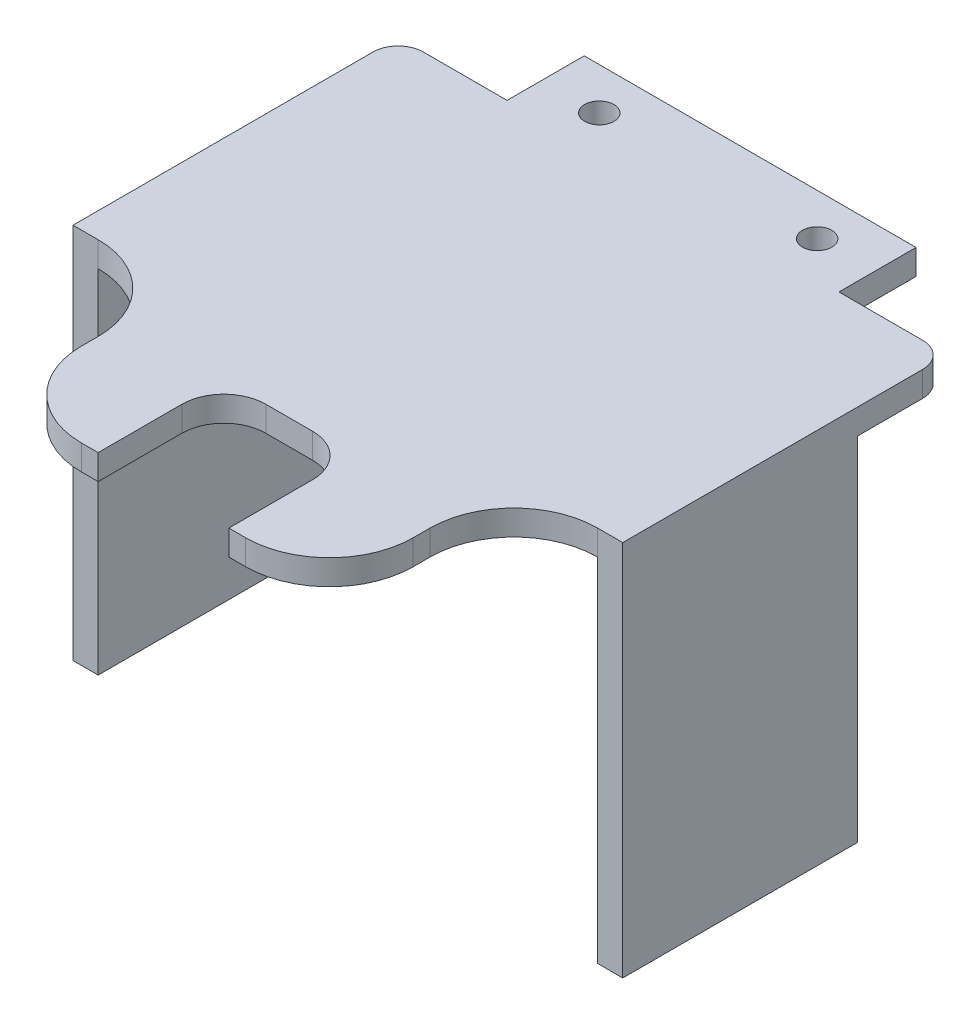
SolidWorks part; units mm, degrees
ref_plane "前视基准面" through (0, 0, 0) normal (0, 0, 1) x (1, 0, 0)
ref_plane "上视基准面" through (0, 0, 0) normal (0, 1, 0) x (1, 0, 0)
ref_plane "右视基准面" through (0, 0, 0) normal (1, 0, 0) x (0, 0, -1)
sketch "草图1" plane through (0, 0, 0) normal (0, 1, 0) x (1, 0, 0)
  line L1 (0, 0) -> (39.6, 0)
  line L2 (0, 0) -> (0, 70)
  line L3 (0, 70) -> (39.6, 70)
  line L4 (39.6, 0) -> (39.6, 70)
  dimension "D1" = 39.6
  dimension "D2" = 70
extrude "凸台-拉伸1" add sketch "草图1" along normal blind 3
sketch "草图2" plane through (0, 3, 0) normal (0, 1, 0) x (1, 0, 0)
  line L0 (39.6, 0) -> (39.6, 70) construction
  line L1 (0, 70) -> (39.6, 70)
  line L2 (0, 70) -> (0, 60)
  line L3 (0, 60) -> (39.6, 60)
  line L4 (39.6, 70) -> (39.6, 60)
  line L5 (0, 65) -> (39.6, 65)
  point P9 (32.8, 65)
  point P10 (6.8, 65)
  point P11 (19.8, 65)
  dimension "D1" = 10
  dimension "D2" = 13
  dimension "D3" = 13
sketch "草图3" plane through (0, 3, 0) normal (0, 1, 0) x (1, 0, 0)
  point P0 (6.8, 65)
  point P3 (32.8, 65)
hole_wizard "孔1" positions "草图3" profile "草图4" legacy end condition up to next
sketch "草图4" plane through (6.8, 3, -65) normal (1, 0, 0) x (0, 0, 1)
  line L0 (0, 0) -> (0, 3)
  line L1 (0, 3) -> (1.75, 3)
  line L2 (1.75, 3) -> (1.75, 0)
  line L3 (1.75, 0) -> (0, 0)
  line L4 (0, 110) -> (0, -10) construction
  dimension "直径" = 3.5
  dimension "深度" = 3
sketch "草图5" plane through (0, 3, 0) normal (0, 1, 0) x (1, 0, 0)
  line L0 (39.6, 0) -> (39.6, 70) construction
  line L1 (39.6, 50) -> (52.6, 50)
  line L2 (39.6, 50) -> (39.6, 22)
  line L3 (39.6, 22) -> (52.6, 22)
  line L4 (52.6, 50) -> (52.6, 22)
  line L5 (0, 60) -> (39.6, 60) construction
  line L6 (0, 70) -> (0, 0) construction
  line L7 (0, 50) -> (-13, 50)
  line L8 (0, 50) -> (0, 22)
  line L9 (0, 22) -> (-13, 22)
  line L10 (-13, 50) -> (-13, 22)
  dimension "D1" = 10
  dimension "D2" = 13
  dimension "D3" = 28
  dimension "D4" = 10
  dimension "D5" = 28
  dimension "D6" = 13
extrude "凸台-拉伸2" add sketch "草图5" against normal blind 3
sketch "草图6" plane through (0, 0, 0) normal (0, -1, 0) x (1, 0, 0)
  line L0 (0, -50) -> (-13, -50) construction
  line L1 (-13, -22) -> (-10, -22)
  line L2 (-13, -22) -> (-13, -50)
  line L3 (-13, -50) -> (-10, -50)
  line L4 (-10, -22) -> (-10, -50)
  line L5 (52.6, -50) -> (39.6, -50) construction
  line L6 (52.6, -22) -> (49.6, -22)
  line L7 (52.6, -22) -> (52.6, -50)
  line L8 (52.6, -50) -> (49.6, -50)
  line L9 (49.6, -22) -> (49.6, -50)
  dimension "D1" = 3
  dimension "D2" = 3
extrude "凸台-拉伸3" add sketch "草图6" along normal blind 42
fillet "圆角1" radius 10 2 edges at (39.6, 1.5, -22) (0, 1.5, -22)
fillet "圆角2" radius 10 2 edges at (39.6, 1.5, 0) (0, 1.5, 0)
sketch "草图7" plane through (0, 3, 0) normal (0, 1, 0) x (1, 0, 0)
  line L0 (0, 70) -> (0, 50) construction
  line L1 (39.6, 50) -> (52.6, 50)
  line L2 (39.6, 50) -> (39.6, 60.8)
  line L3 (39.6, 60.8) -> (52.6, 60.8)
  line L4 (52.6, 50) -> (52.6, 60.8)
  line L5 (-13, 50) -> (0, 50)
  line L6 (-13, 50) -> (-13, 60.8)
  line L7 (-13, 60.8) -> (0, 60.8)
  line L8 (0, 50) -> (0, 60.8)
  dimension "D1" = 13
  dimension "D2" = 10.8
  dimension "D3" = 10.8
extrude "凸台-拉伸4" add sketch "草图7" against normal blind 3
fillet "圆角4" radius 3 2 edges at (52.6, 1.5, -60.8) (-13, 1.5, -60.8)
sketch "草图8" plane through (0, 3, 0) normal (0, 1, 0) x (1, 0, 0)
  line L0 (10, 0) -> (29.6, 0) construction
  line L1 (12, 0) -> (27.6, 0)
  line L2 (12, 0) -> (12, 15)
  line L3 (12, 15) -> (27.6, 15)
  line L4 (27.6, 0) -> (27.6, 15)
  line L5 (39.6, 10) -> (39.6, 12) construction
  line L6 (0, 12) -> (0, 10) construction
  dimension "D1" = 12
  dimension "D2" = 12
  dimension "D3" = 15
extrude "切除-拉伸1" cut sketch "草图8" against normal through all
fillet "圆角5" radius 5 2 edges at (27.6, 1.5, -15) (12, 1.5, -15)
